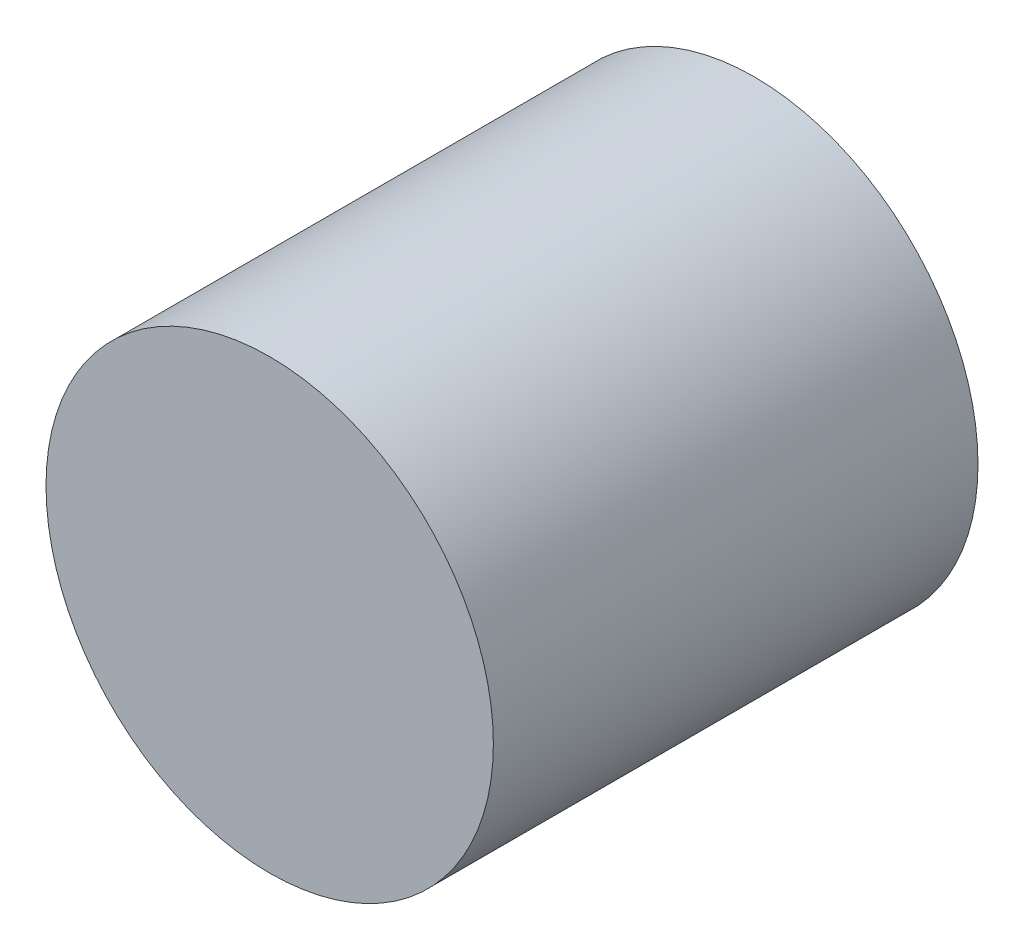
SolidWorks part; units mm, degrees
ref_plane "Front Plane" through (0, 0, 0) normal (0, 0, 1) x (1, 0, 0)
ref_plane "Top Plane" through (0, 0, 0) normal (0, 1, 0) x (1, 0, 0)
ref_plane "Right Plane" through (0, 0, 0) normal (1, 0, 0) x (0, 0, -1)
sketch "Sketch1" plane through (0, 0, 0) normal (0, 0, 1) x (1, 0, 0)
  circle A0 centre (6, 6) radius 6
  dimension "D1" = 12
extrude "Profile" add sketch "Sketch1" along normal blind 13
equation "\"Profile_Depth\"= 13mm"
equation "\"D1@Profile\" = \"Profile_Depth\""
equation "\"Profile_Sketch_1\"= 12mm"
equation "\"D1@Sketch1\" = \"Profile_Sketch_1\""
equation "\"EnvelopeWidth\"= 12mm"
equation "\"EnvelopeHeight\"= 12mm"
